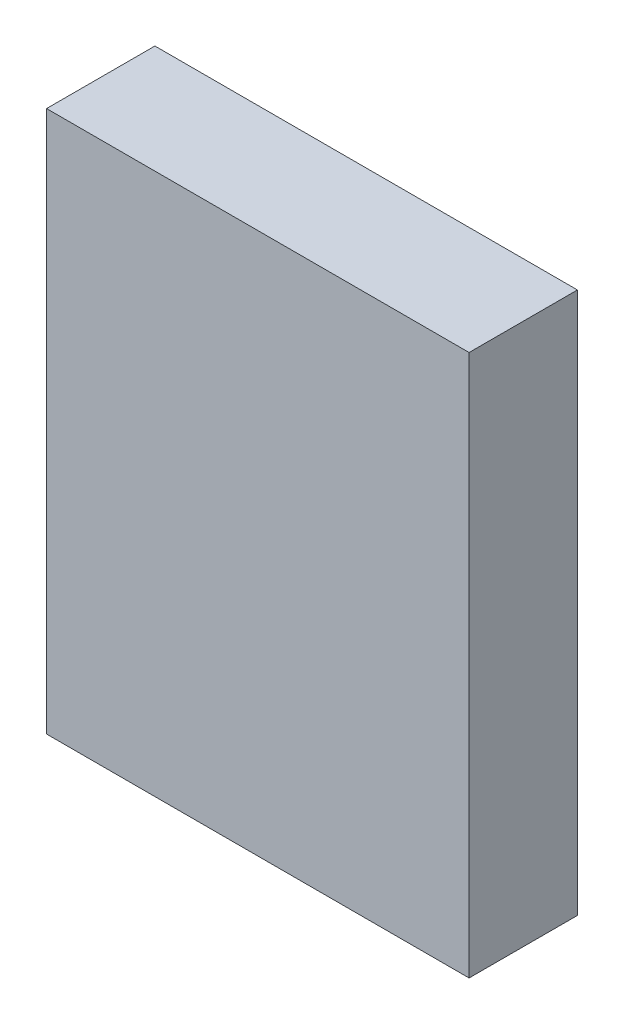
SolidWorks part; units mm, degrees
ref_plane "Front Plane" through (0, 0, 0) normal (0, 0, 1) x (1, 0, 0)
ref_plane "Top Plane" through (0, 0, 0) normal (0, 1, 0) x (1, 0, 0)
ref_plane "Right Plane" through (0, 0, 0) normal (1, 0, 0) x (0, 0, -1)
sketch "Sketch1" plane through (0, 0, 0) normal (0, 0, 1) x (1, 0, 0)
  line L1 (-1.95, 2.5) -> (1.95, 2.5)
  line L2 (-1.95, 2.5) -> (-1.95, -2.5)
  line L3 (-1.95, -2.5) -> (1.95, -2.5)
  line L4 (1.95, 2.5) -> (1.95, -2.5)
  line L5 (-1.95, 2.5) -> (1.95, -2.5) construction
  line L6 (-1.95, -2.5) -> (1.95, 2.5) construction
  point P0 (0, 0)
  dimension "D1" = 3.9
  dimension "D2" = 5
extrude "Boss-Extrude1" add sketch "Sketch1" along normal blind 1
